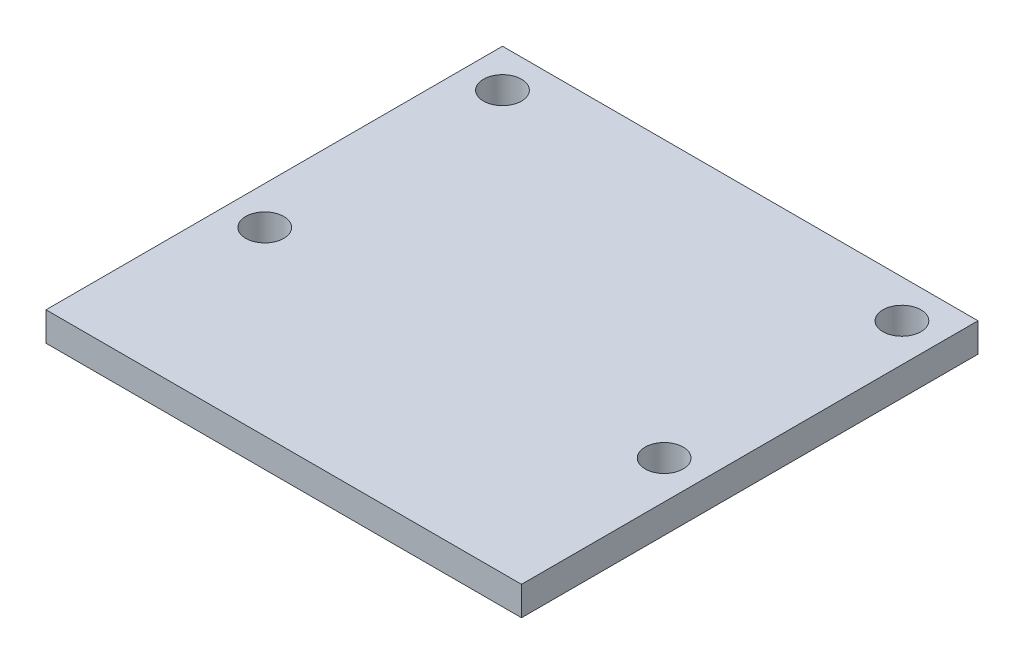
SolidWorks part; units mm, degrees
ref_plane "Front Plane" through (0, 0, 0) normal (0, 0, 1) x (1, 0, 0)
ref_plane "Top Plane" through (0, 0, 0) normal (0, 1, 0) x (1, 0, 0)
ref_plane "Right Plane" through (0, 0, 0) normal (1, 0, 0) x (0, 0, -1)
sketch "Sketch2" plane through (0, 0, 0) normal (0, 1, 0) x (1, 0, 0)
  line L0 (2, 22) -> (0, 22) construction
  line L1 (0, 0) -> (25, 0)
  line L2 (0, 0) -> (0, 24)
  line L3 (0, 24) -> (25, 24)
  line L4 (25, 0) -> (25, 24)
  line L5 (2, 22) -> (23, 22) construction
  line L6 (2, 22) -> (2, 9.5) construction
  line L7 (2, 9.5) -> (23, 9.5) construction
  line L8 (23, 22) -> (23, 9.5) construction
  line L9 (23, 22) -> (25, 22) construction
  circle A0 centre (2, 22) radius 1
  circle A1 centre (23, 22) radius 1
  circle A2 centre (23, 9.5) radius 1
  circle A3 centre (2, 9.5) radius 1
  dimension "D6" = 2
  dimension "D1" = 25
  dimension "D2" = 24
  dimension "D3" = 21
  dimension "D4" = 12.5
  dimension "D5" = 2
extrude "Boss-Extrude1" add sketch "Sketch2" along normal blind 1.524
